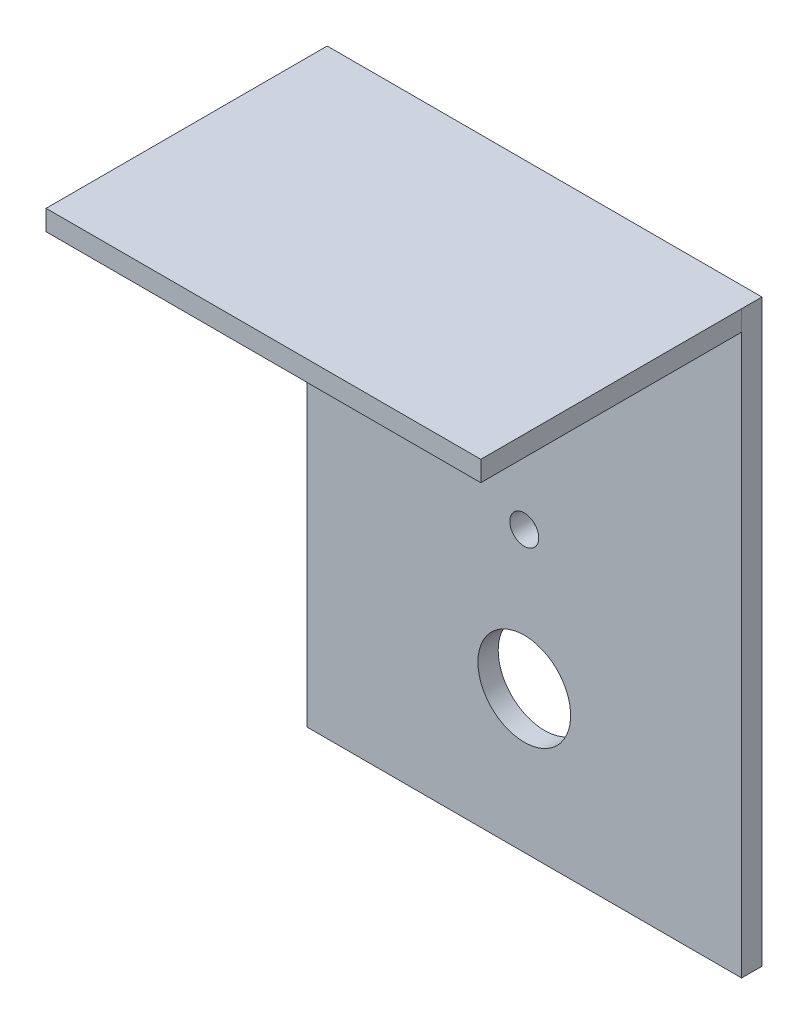
SolidWorks part; units mm, degrees
ref_plane "Front Plane" through (0, 0, 0) normal (0, 0, 1) x (1, 0, 0)
ref_plane "Top Plane" through (0, 0, 0) normal (0, 1, 0) x (1, 0, 0)
ref_plane "Right Plane" through (0, 0, 0) normal (1, 0, 0) x (0, 0, -1)
sketch "Sketch1" plane through (0, 0, 0) normal (0, 1, 0) x (1, 0, 0)
  line L1 (0, 0) -> (75, 0)
  line L2 (0, 0) -> (0, 45)
  line L3 (0, 45) -> (75, 45)
  line L4 (75, 0) -> (75, 45)
  dimension "D1" = 45
  dimension "D2" = 75
extrude "Boss-Extrude1" add sketch "Sketch1" along normal blind 3.5 contours L3 L4 L1 L2
sketch "Sketch2" plane through (0, 0, -45) normal (0, 0, -1) x (-1, 0, 0)
  line L1 (0, 3.5) -> (-74.9993, 3.5)
  line L2 (0, 3.5) -> (0, -96.5)
  line L3 (0, -96.5) -> (-74.9993, -96.5)
  line L4 (-74.9993, 3.5) -> (-74.9993, -96.5)
  dimension "D1" = 100
extrude "Boss-Extrude2" add sketch "Sketch2" along normal blind 3.5
sketch "Sketch3" plane through (0, 0, -48.5) normal (0, 0, -1) x (-1, 0, 0)
  line L0 (-37.5, 3.5) -> (-37.4997, -96.5) construction
  line L1 (0, 3.5) -> (-75, 3.5) construction
  line L2 (-74.9993, -96.5) -> (0, -96.5) construction
  line L3 (0, -48.25) -> (-74.9993, -48.25) construction
  line L4 (0, -96.5) -> (0, 0) construction
  line L5 (-74.9993, 0) -> (-74.9993, -96.5) construction
  circle A0 centre (-37.4999, -24.4706) radius 8
  circle A1 centre (-37.4999, -72.0294) radius 8
  circle A2 centre (-37.4997, -48.25) radius 2.5
  point P18 (0, 0)
  point P19 (0, 0)
  dimension "D1" = 16
  dimension "D2" = 5
extrude "Cut-Extrude2" cut sketch "Sketch3" against normal through all
